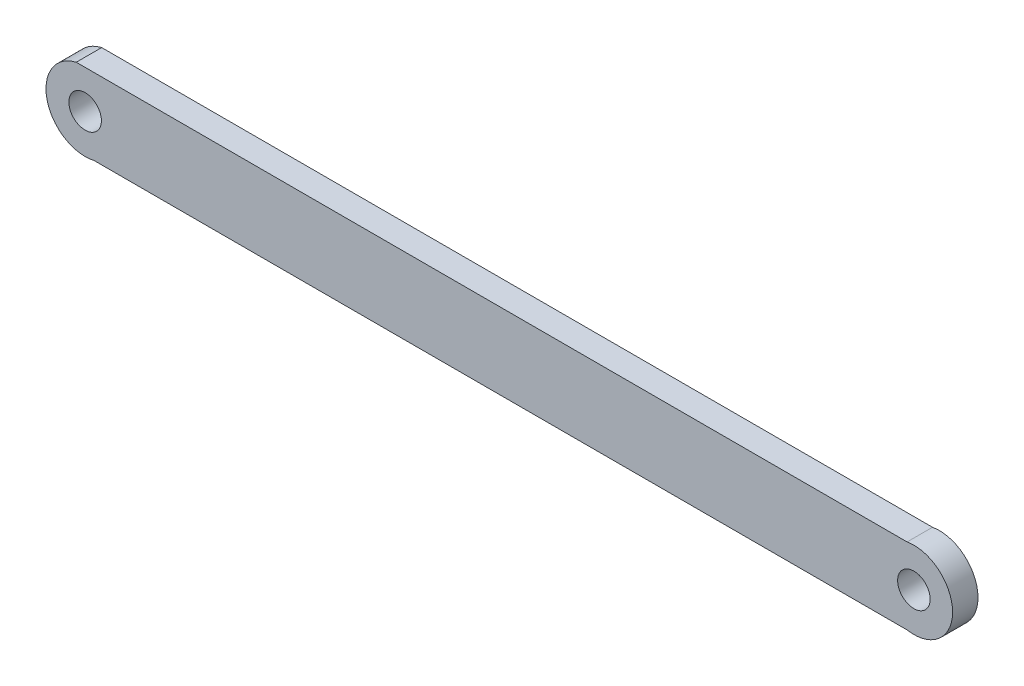
SolidWorks part; units mm, degrees
ref_plane "Front Plane" through (0, 0, 0) normal (0, 0, 1) x (1, 0, 0)
ref_plane "Top Plane" through (0, 0, 0) normal (0, 1, 0) x (1, 0, 0)
ref_plane "Right Plane" through (0, 0, 0) normal (1, 0, 0) x (0, 0, -1)
sketch "Sketch1" plane through (0, 0, 0) normal (0, 0, 1) x (1, 0, 0)
  line L1 (-51.9099, 4.6876) -> (51.9099, 4.6876)
  line L3 (-49.6901, -4.8374) -> (51.9099, -4.8374)
  arc A0 (51.9099, -4.8374) -> (51.9099, 4.6876) centre (52.7577, -0.0749) ccw
  arc A1 (-51.9099, 4.6876) -> (-49.6901, -4.8374) centre (-50.8, -0.0749) ccw
  circle A2 centre (-50.8, -0.0749) radius 2.032
  circle A3 centre (52.7577, -0.0749) radius 2.032
  point P0 (0, 0)
  dimension "D1" = 9.525
  dimension "D2" = 101.6
extrude "Extrude1" add sketch "Sketch1" along normal blind 3.175
